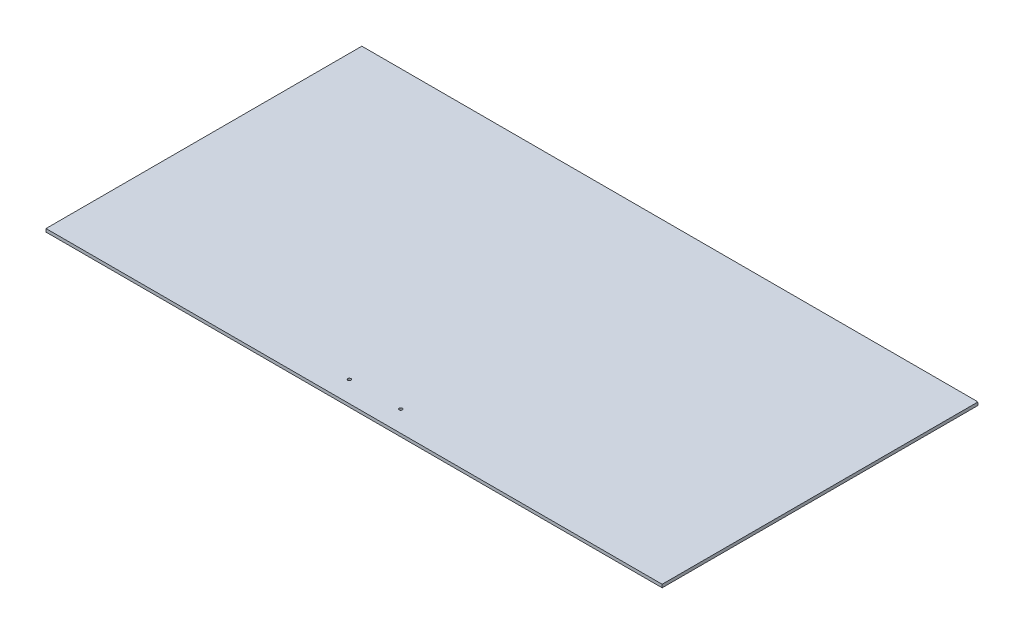
SolidWorks part; units mm, degrees
material "Acrylic (Medium-high impact)"
ref_plane "Front" through (0, 0, 0) normal (0, 0, 1) x (1, 0, 0)
ref_plane "Top" through (0, 0, 0) normal (0, 1, 0) x (1, 0, 0)
ref_plane "Right" through (0, 0, 0) normal (1, 0, 0) x (0, 0, -1)
sketch "Sketch1" plane through (0, 0, 0) normal (0, 1, 0) x (1, 0, 0)
  line L1 (-628.65, 322.2625) -> (628.65, 322.2625)
  line L2 (-628.65, 322.2625) -> (-628.65, -322.2625)
  line L3 (-628.65, -322.2625) -> (628.65, -322.2625)
  line L4 (628.65, 322.2625) -> (628.65, -322.2625)
  line L5 (-628.65, 322.2625) -> (628.65, -322.2625) construction
  line L6 (-628.65, -322.2625) -> (628.65, 322.2625) construction
  point P0 (0, 0)
  dimension "D1" = 1257.3
  dimension "D2" = 644.525
extrude "Boss-Extrude1" add sketch "Sketch1" along normal blind 6.35
sketch "Sketch2" plane through (0, 6.35, 0) normal (0, 1, 0) x (1, 0, 0)
  line L0 (0, 0) -> (0, -279.4) construction
  line L1 (-52.3875, -279.4) -> (52.3875, -279.4) construction
  circle A0 centre (-52.3875, -279.4) radius 3.175
  circle A1 centre (52.3875, -279.4) radius 3.175
  point P5 (0, -279.4)
  dimension "D3" = 6.35
  dimension "D1" = 279.4
  dimension "D2" = 104.775
extrude "Cut-Extrude1" cut sketch "Sketch2" against normal through all
sketch "Sketch3" plane through (628.65, 0, 0) normal (1, 0, 0) x (0, 0, -1)
  line L0 (-322.2625, 0) -> (322.2625, 0) construction
  line L1 (322.2625, 6.35) -> (322.2625, 0) construction
  circle A0 centre (323.5325, 7.62) radius 2.54
  point P2 (323.684, 7.9272)
  dimension "D1" = 5.08
  dimension "D2" = 7.62
  dimension "D3" = 1.27
extrude "Cut-Extrude2" cut sketch "Sketch3" against normal blind 2.54
